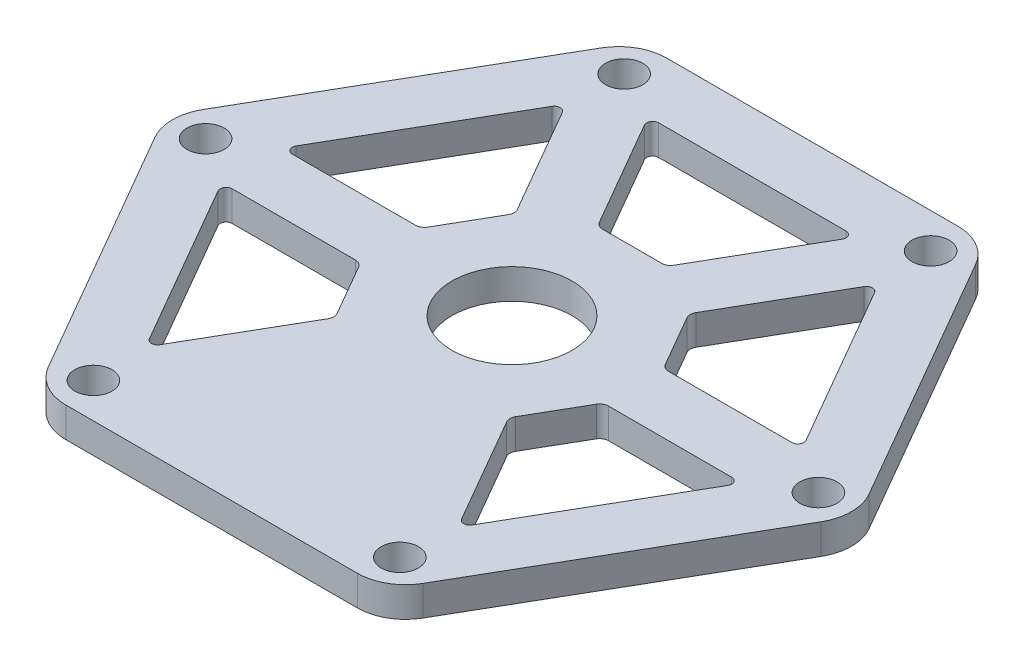
SolidWorks part; units mm, degrees
ref_plane "Front Plane" through (0, 0, 0) normal (0, 0, 1) x (1, 0, 0)
ref_plane "Top Plane" through (0, 0, 0) normal (0, 1, 0) x (1, 0, 0)
ref_plane "Right Plane" through (0, 0, 0) normal (1, 0, 0) x (0, 0, -1)
sketch "Sketch1" plane through (0, 0, 0) normal (0, 1, 0) x (1, 0, 0)
  line L1 (-57.735, 0) -> (-28.8675, -50)
  line L2 (-28.8675, -50) -> (28.8675, -50)
  line L3 (28.8675, -50) -> (57.735, 0)
  line L4 (57.735, 0) -> (28.8675, 50)
  line L5 (28.8675, 50) -> (-28.8675, 50)
  line L6 (-28.8675, 50) -> (-57.735, 0)
  circle A0 centre (0, 0) radius 50 construction
  circle A1 centre (0, 0) radius 50 construction
  dimension "D2" = 100
  dimension "D1" = 100
extrude "Boss-Extrude1" add sketch "Sketch1" along normal blind 5
fillet "Fillet1" radius 8 6 edges at (28.8675, 2.5, -50) (57.735, 2.5, 0) (28.8675, 2.5, 50) (-28.8675, 2.5, 50) (-57.735, 2.5, 0) (-28.8675, 2.5, -50)
sketch "Sketch2" plane through (0, 5, 0) normal (0, 1, 0) x (1, 0, 0)
  line L0 (0, 30) -> (0, 20) construction
  line L1 (0, 40) -> (0, 50) construction
  line L2 (6.2065, 20.75) -> (16.4545, 38.5)
  line L3 (15.5885, 40) -> (-15.5885, 40)
  line L4 (-16.4545, 38.5) -> (-6.2065, 20.75)
  line L5 (24.2487, 50) -> (-24.2487, 50) construction
  line L36 (4.9075, 20) -> (-4.9075, 20)
  line L37 (21.0733, 5) -> (41.5692, 5)
  line L38 (42.4352, 6.5) -> (26.8468, 33.5)
  line L39 (25.1147, 33.5) -> (14.8668, 15.75)
  line L40 (19.7742, 5.75) -> (14.8668, 14.25)
  line L41 (14.8668, -15.75) -> (25.1147, -33.5)
  line L42 (26.8468, -33.5) -> (42.4352, -6.5)
  line L43 (41.5692, -5) -> (21.0733, -5)
  line L44 (14.8668, -14.25) -> (19.7742, -5.75)
  line L45 (-6.2065, -20.75) -> (-16.4545, -38.5) construction
  line L46 (-15.5885, -40) -> (15.5885, -40) construction
  line L47 (16.4545, -38.5) -> (6.2065, -20.75) construction
  line L48 (-4.9075, -20) -> (4.9075, -20) construction
  line L49 (-21.0733, -5) -> (-41.5692, -5)
  line L50 (-42.4352, -6.5) -> (-26.8468, -33.5)
  line L51 (-25.1147, -33.5) -> (-14.8668, -15.75)
  line L52 (-19.7742, -5.75) -> (-14.8668, -14.25)
  line L53 (-14.8668, 15.75) -> (-25.1147, 33.5)
  line L54 (-26.8468, 33.5) -> (-42.4352, 6.5)
  line L55 (-41.5692, 5) -> (-21.0733, 5)
  line L56 (-14.8668, 14.25) -> (-19.7742, 5.75)
  line L57 (0, 0) -> (-25.5, 44.1673) construction
  circle A0 centre (0, 0) radius 10
  circle A1 centre (0, 30) radius 10 construction
  arc A3 (-15.5885, 40) -> (-16.4545, 38.5) centre (-15.5885, 39) ccw
  arc A4 (16.4545, 38.5) -> (15.5885, 40) centre (15.5885, 39) ccw
  arc A5 (4.9075, 20) -> (6.2065, 20.75) centre (4.9075, 21.5) ccw
  arc A6 (-4.9075, 20) -> (-6.2065, 20.75) centre (-4.9075, 21.5) cw
  arc A7 (19.7742, 5.75) -> (21.0733, 5) centre (21.0733, 6.5) ccw
  arc A8 (41.5692, 5) -> (42.4352, 6.5) centre (41.5692, 6) ccw
  arc A9 (26.8468, 33.5) -> (25.1147, 33.5) centre (25.9808, 33) ccw
  arc A10 (14.8668, 14.25) -> (14.8668, 15.75) centre (16.1658, 15) cw
  arc A11 (14.8668, -14.25) -> (14.8668, -15.75) centre (16.1658, -15) ccw
  arc A12 (25.1147, -33.5) -> (26.8468, -33.5) centre (25.9808, -33) ccw
  arc A13 (42.4352, -6.5) -> (41.5692, -5) centre (41.5692, -6) ccw
  arc A14 (19.7742, -5.75) -> (21.0733, -5) centre (21.0733, -6.5) cw
  arc A15 (-4.9075, -20) -> (-6.2065, -20.75) centre (-4.9075, -21.5) ccw construction
  arc A16 (-16.4545, -38.5) -> (-15.5885, -40) centre (-15.5885, -39) ccw construction
  arc A17 (15.5885, -40) -> (16.4545, -38.5) centre (15.5885, -39) ccw construction
  arc A18 (4.9075, -20) -> (6.2065, -20.75) centre (4.9075, -21.5) cw construction
  arc A19 (-19.7742, -5.75) -> (-21.0733, -5) centre (-21.0733, -6.5) ccw
  arc A20 (-41.5692, -5) -> (-42.4352, -6.5) centre (-41.5692, -6) ccw
  arc A21 (-26.8468, -33.5) -> (-25.1147, -33.5) centre (-25.9808, -33) ccw
  arc A22 (-14.8668, -14.25) -> (-14.8668, -15.75) centre (-16.1658, -15) cw
  arc A23 (-14.8668, 14.25) -> (-14.8668, 15.75) centre (-16.1658, 15) ccw
  arc A24 (-25.1147, 33.5) -> (-26.8468, 33.5) centre (-25.9808, 33) ccw
  arc A25 (-42.4352, 6.5) -> (-41.5692, 5) centre (-41.5692, 6) ccw
  arc A26 (-19.7742, 5.75) -> (-21.0733, 5) centre (-21.0733, 6.5) cw
  circle A27 centre (-25.5, 44.1673) radius 3.1
  circle A28 centre (25.5, 44.1673) radius 3.1
  circle A29 centre (51, 0) radius 3.1
  circle A30 centre (25.5, -44.1673) radius 3.1
  circle A31 centre (-25.5, -44.1673) radius 3.1
  circle A32 centre (-51, 0) radius 3.1
  point P19 (0, 20)
  point P30 (0, 0)
  point P66 (0, 0)
  point P88 (0, 0)
  point P101 (0, 0)
  dimension "D1" = 20
  dimension "D3" = 20
  dimension "D6" = 1
  dimension "D8" = 1.5
  dimension "D11" = 6.2
  dimension "D2" = 30
  dimension "D4" = 10
  dimension "D5" = 10
  dimension "D7" = 20
  dimension "D10" = 51
  dimension "D9" = 6
  dimension "D12" = 6
extrude "Cut-Extrude1" cut sketch "Sketch2" against normal blind 10
